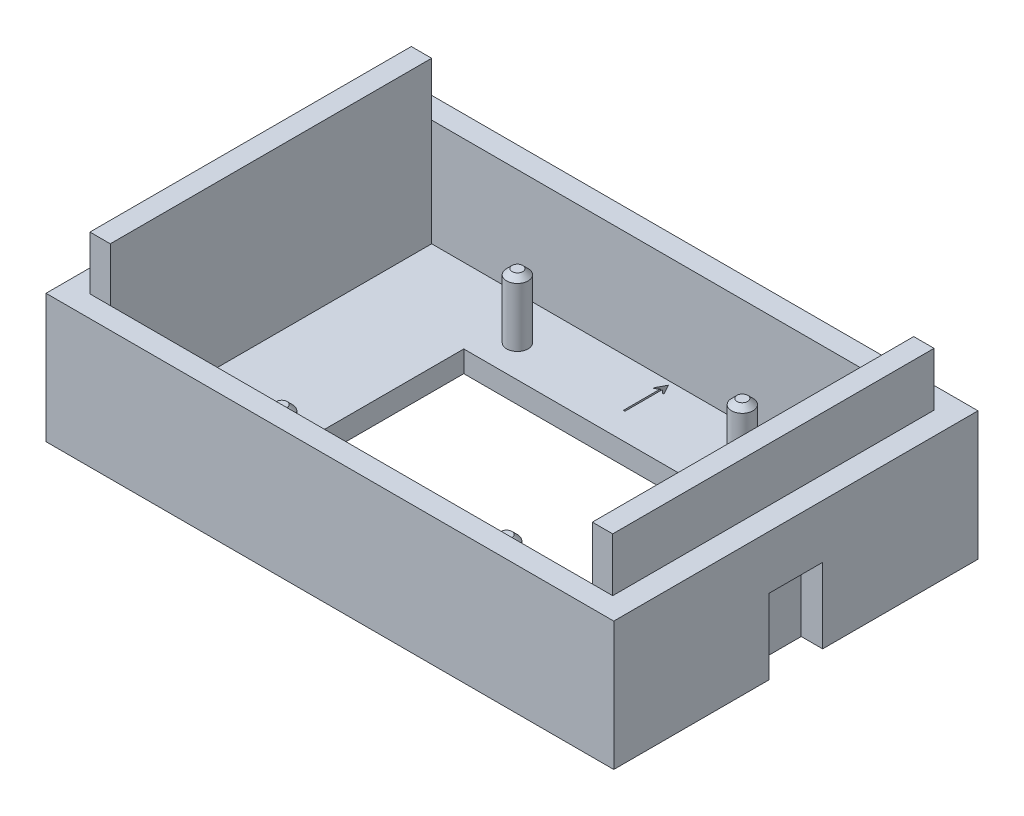
SolidWorks part; units mm, degrees
ref_plane "前视基准面" through (0, 0, 0) normal (0, 0, 1) x (1, 0, 0)
ref_plane "上视基准面" through (0, 0, 0) normal (0, 1, 0) x (1, 0, 0)
ref_plane "右视基准面" through (0, 0, 0) normal (1, 0, 0) x (0, 0, -1)
other "Configuration Table"
sketch "草图1" plane through (0, 0, 0) normal (0, 1, 0) x (1, 0, 0)
  line L1 (0, 0) -> (29, 0)
  line L2 (0, 0) -> (0, 30)
  line L3 (0, 30) -> (29, 30)
  line L4 (29, 0) -> (29, 30)
  line L5 (2, 23) -> (27, 23)
  line L6 (2, 23) -> (2, 6)
  line L7 (2, 6) -> (27, 6)
  line L8 (27, 23) -> (27, 6)
  dimension "D1" = 29
  dimension "D2" = 30
  dimension "D3" = 2
  dimension "D4" = 2
  dimension "D5" = 6
  dimension "D6" = 7
extrude "凸台-拉伸1" add sketch "草图1" along normal blind 2
sketch "草图4" plane through (0, 2, 0) normal (0, 1, 0) x (1, 0, 0)
  line L0 (29, 30) -> (0, 30) construction
  line L1 (0, 30) -> (0, 0) construction
  circle A0 centre (4, 26) radius 1
  dimension "D3" = 2
  dimension "D1" = 4
  dimension "D2" = 4
extrude "凸台-拉伸2" add sketch "草图4" along normal blind 6
chamfer "倒角1" distance 0.5 angle 45 1 edges at (4, 8, -25)
pattern_linear "阵列(线性)1" count 2 spacing 21 along (1, 0, 0) count 2 spacing 22 along (0, 0, 1) of "凸台-拉伸2", "倒角1"
sketch "草图5" plane through (0, 0, 0) normal (0, -1, 0) x (1, 0, 0)
  line L0 (0, 0) -> (29, 0) construction
  line L1 (29, 0) -> (29, -30) construction
  line L2 (29, -30) -> (0, -30) construction
  line L3 (0, -30) -> (0, 0) construction
  line L4 (0, 0) -> (29, 0)
  line L5 (29, 0) -> (29, -30)
  line L6 (29, -30) -> (0, -30)
  line L7 (0, -30) -> (0, 0)
  line L9 (-12, -32) -> (41, -32)
  line L10 (-12, -32) -> (-12, 2)
  line L11 (-12, 2) -> (41, 2)
  line L12 (41, -32) -> (41, 2)
  dimension "D1" = 2
  dimension "D2" = 12
  dimension "D3" = 2
  dimension "D4" = 12
extrude "凸台-拉伸3" add sketch "草图5" against normal up to surface (2 mm away) up to face at (25, 2, -27)
sketch "草图6" plane through (0, 2, 0) normal (0, 1, 0) x (1, 0, 0)
  line L0 (41, -2) -> (41, 32) construction
  line L1 (-12, -2) -> (41, -2) construction
  line L2 (-12, 32) -> (-12, -2) construction
  line L3 (41, 32) -> (-12, 32) construction
  line L4 (41, -2) -> (41, 32)
  line L5 (-12, -2) -> (41, -2)
  line L6 (-12, 32) -> (-12, -2)
  line L7 (41, 32) -> (-12, 32)
  line L9 (-8, 30) -> (37, 30)
  line L10 (-8, 30) -> (-8, 0)
  line L11 (-8, 0) -> (37, 0)
  line L12 (37, 30) -> (37, 0)
  dimension "D1" = 4
  dimension "D2" = 4
  dimension "D3" = 2
  dimension "D4" = 2
extrude "凸台-拉伸4" add sketch "草图6" along normal blind 10
sketch "草图7" plane through (0, 12, 0) normal (0, 1, 0) x (1, 0, 0)
  line L0 (-8, 0) -> (37, 0) construction
  line L1 (-8, 30) -> (-9.9, 30)
  line L2 (-8, 30) -> (-8, 0)
  line L3 (-8, 0) -> (-9.9, 0)
  line L4 (-9.9, 30) -> (-9.9, 0)
  line L5 (-12, 32) -> (-12, -2) construction
  line L6 (14.5, 30) -> (14.5, 0) construction
  line L7 (37, 30) -> (-8, 30) construction
  line L8 (-8, 0) -> (37, 0) construction
  line L9 (38.9, 30) -> (38.9, 0)
  line L10 (37, 0) -> (38.9, 0)
  line L11 (37, 30) -> (37, 0)
  line L12 (37, 30) -> (38.9, 30)
  dimension "D1" = 2.1
extrude "凸台-拉伸5" add sketch "草图7" along normal blind 5
sketch "草图8" plane through (-12, 0, 0) normal (-1, 0, 0) x (0, 0, 1)
  line L0 (-15, 12) -> (-15, 0) construction
  line L1 (-32, 12) -> (2, 12) construction
  line L2 (2, 0) -> (-32, 0) construction
  line L3 (-30, 12) -> (0, 12) construction
  line L4 (-17.5, 7) -> (-12.5, 7)
  line L5 (-17.5, 7) -> (-17.5, 0)
  line L6 (-17.5, 0) -> (-12.5, 0)
  line L7 (-12.5, 7) -> (-12.5, 0)
  dimension "D1" = 5
  dimension "D2" = 5
extrude "切除-拉伸1" cut sketch "草图8" against normal blind 2
sketch "草图9" plane through (0, 2, 0) normal (0, 1, 0) x (1, 0, 0)
  line L0 (4, 26) -> (25, 26) construction
  text T0 "↑"
extrude "切除-拉伸2" cut sketch "草图9" against normal blind 1
ref_plane "基准面1" through (14.5, 0, 0) normal (-1, 0, 0) x (0, 0, 1)
mirror "镜向1" about plane through (14.5, 0, 0) normal (-1, 0, 0) of "切除-拉伸1"
